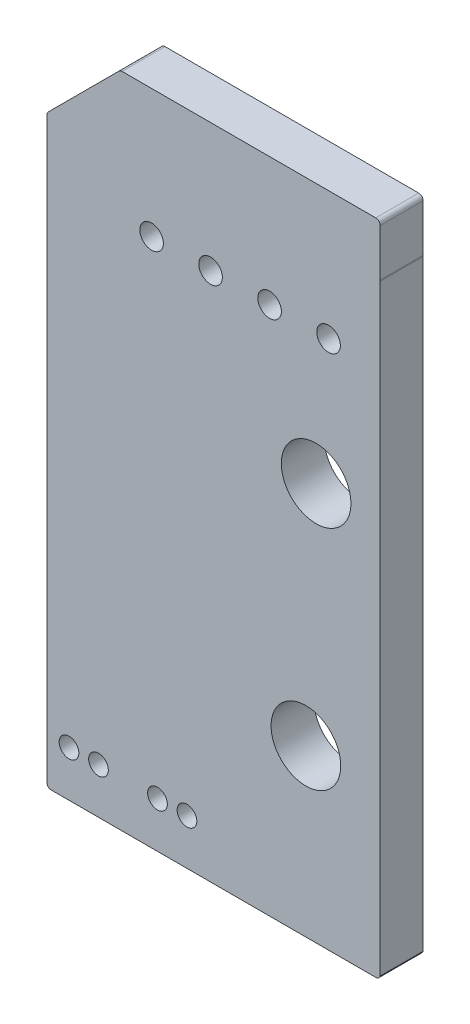
SolidWorks part; units mm, degrees
ref_plane "Front Plane" through (0, 0, 0) normal (0, 0, 1) x (1, 0, 0)
ref_plane "Top Plane" through (0, 0, 0) normal (0, 1, 0) x (1, 0, 0)
ref_plane "Right Plane" through (0, 0, 0) normal (1, 0, 0) x (0, 0, -1)
sketch "Sketch1" plane through (0, 0, 0) normal (0, 0, 1) x (1, 0, 0)
  line L0 (1415.2448, -839.5945) -> (1429.2148, -839.5945)
  line L1 (1415.2448, -839.2135) -> (1429.2148, -839.2135)
  line L2 (1415.4353, -839.404) -> (1415.4353, -814.512)
  line L3 (1415.0543, -839.404) -> (1415.0543, -814.512)
  line L4 (1418.2928, -811.6545) -> (1429.2148, -811.6545)
  line L5 (1418.2928, -811.2735) -> (1429.2148, -811.2735)
  line L6 (1415.3795, -814.6467) -> (1418.4275, -811.5987)
  line L7 (1415.1101, -814.3773) -> (1418.1581, -811.3293)
  line L8 (1429.4053, -813.496) -> (1429.4053, -811.464)
  line L9 (1429.0243, -813.496) -> (1429.0243, -811.464)
  line L10 (1429.3977, -839.4624) -> (1429.3977, -813.463)
  line L11 (1429.0167, -839.4624) -> (1429.0167, -813.463)
  line L12 (1415.7071, -837.3263) -> (1416.3065, -837.9257)
  line L13 (1416.3065, -837.3263) -> (1415.7071, -837.9257)
  line L14 (1416.9771, -837.3263) -> (1417.5765, -837.9257)
  line L15 (1417.5765, -837.3263) -> (1416.9771, -837.9257)
  line L16 (1419.5171, -837.3263) -> (1420.1165, -837.9257)
  line L17 (1420.1165, -837.3263) -> (1419.5171, -837.9257)
  line L18 (1420.7871, -837.3263) -> (1421.3865, -837.9257)
  line L19 (1421.3865, -837.3263) -> (1420.7871, -837.9257)
  line L20 (1419.5628, -816.29) -> (1419.5628, -817.306)
  line L21 (1419.0548, -816.798) -> (1420.0708, -816.798)
  line L22 (1422.1028, -816.29) -> (1422.1028, -817.306)
  line L23 (1421.5948, -816.798) -> (1422.6108, -816.798)
  line L24 (1424.6428, -816.29) -> (1424.6428, -817.306)
  line L25 (1424.1348, -816.798) -> (1425.1508, -816.798)
  line L26 (1427.1828, -816.29) -> (1427.1828, -817.306)
  line L27 (1426.6748, -816.798) -> (1427.6908, -816.798)
  line L28 (1427.268, -823.5228) -> (1427.268, -821.4016)
  line L29 (1427.268, -821.4016) -> (1425.1469, -821.4016)
  line L30 (1425.1469, -821.4016) -> (1425.1469, -823.5228)
  line L31 (1425.1469, -823.5228) -> (1427.268, -823.5228)
  line L32 (1427.268, -833.5228) -> (1427.268, -831.4016)
  line L33 (1427.268, -831.4016) -> (1425.1469, -831.4016)
  line L34 (1425.1469, -831.4016) -> (1425.1469, -833.5228)
  line L35 (1425.1469, -833.5228) -> (1427.268, -833.5228)
  line L36 (-6.985, -14.1313) -> (6.985, -14.1313)
  line L39 (-7.1755, -13.9408) -> (-7.1755, 10.9512)
  line L41 (-3.937, 14.1897) -> (6.985, 14.1897)
  line L43 (-7.1197, 11.0859) -> (-4.0717, 14.1339)
  line L44 (7.1755, 11.9672) -> (7.1755, 13.9992)
  line L46 (7.1679, -13.9992) -> (7.1679, 11.9139)
  line L48 (-6.5227, -11.8631) -> (-5.9233, -12.4625) construction
  line L49 (-5.9233, -11.8631) -> (-6.5227, -12.4625) construction
  line L50 (-5.2527, -11.8631) -> (-4.6533, -12.4625) construction
  line L51 (-4.6533, -11.8631) -> (-5.2527, -12.4625) construction
  line L52 (-2.7127, -11.8631) -> (-2.1133, -12.4625) construction
  line L53 (-2.1133, -11.8631) -> (-2.7127, -12.4625) construction
  line L54 (-1.4427, -11.8631) -> (-0.8433, -12.4625) construction
  line L55 (-0.8433, -11.8631) -> (-1.4427, -12.4625) construction
  line L56 (-2.667, 9.1732) -> (-2.667, 8.1572) construction
  line L57 (-3.175, 8.6652) -> (-2.159, 8.6652) construction
  line L58 (-0.127, 9.1732) -> (-0.127, 8.1572) construction
  line L59 (-0.635, 8.6652) -> (0.381, 8.6652) construction
  line L60 (2.413, 9.1732) -> (2.413, 8.1572) construction
  line L61 (1.905, 8.6652) -> (2.921, 8.6652) construction
  line L62 (4.953, 9.1732) -> (4.953, 8.1572) construction
  line L63 (4.445, 8.6652) -> (5.461, 8.6652) construction
  line L64 (5.9169, 1.9404) -> (5.9169, 3.001) construction
  line L65 (5.9169, 3.001) -> (2.9171, 3.001) construction
  line L66 (2.9171, 3.001) -> (2.9171, 1.9404) construction
  line L67 (2.9171, 1.9404) -> (5.9169, 1.9404) construction
  line L68 (5.0382, -8.0596) -> (5.0382, -5.9384) construction
  line L69 (5.0382, -5.9384) -> (2.9171, -5.9384) construction
  line L70 (2.9171, -5.9384) -> (2.9171, -8.0596) construction
  line L71 (2.9171, -8.0596) -> (5.0382, -8.0596) construction
  arc A0 (1429.2148, -839.5945) -> (1429.2148, -839.2135) centre (1429.2148, -839.404) ccw
  arc A1 (1415.2448, -839.2135) -> (1415.2448, -839.5945) centre (1415.2448, -839.404) ccw
  arc A2 (1415.4353, -814.512) -> (1415.0543, -814.512) centre (1415.2448, -814.512) ccw
  arc A3 (1415.0543, -839.404) -> (1415.4353, -839.404) centre (1415.2448, -839.404) ccw
  arc A4 (1429.2148, -811.6545) -> (1429.2148, -811.2735) centre (1429.2148, -811.464) ccw
  arc A5 (1418.2928, -811.2735) -> (1418.2928, -811.6545) centre (1418.2928, -811.464) ccw
  arc A6 (1418.4275, -811.5987) -> (1418.1581, -811.3293) centre (1418.2928, -811.464) ccw
  arc A7 (1415.1101, -814.3773) -> (1415.3795, -814.6467) centre (1415.2448, -814.512) ccw
  arc A8 (1429.4053, -811.464) -> (1429.0243, -811.464) centre (1429.2148, -811.464) ccw
  arc A9 (1429.0243, -813.496) -> (1429.4053, -813.496) centre (1429.2148, -813.496) ccw
  arc A10 (1429.3977, -813.463) -> (1429.0167, -813.463) centre (1429.2072, -813.463) ccw
  arc A11 (1429.0167, -839.4624) -> (1429.3977, -839.4624) centre (1429.2072, -839.4624) ccw
  circle A12 centre (1419.7076, -828.162) radius 0.3175
  circle A13 centre (1421.1579, -828.0629) radius 0.3175
  arc A14 (6.985, -14.1313) -> (7.1679, -13.9941) centre (6.985, -13.9408) ccw
  arc A15 (-7.1755, -13.9408) -> (-6.985, -14.1313) centre (-6.985, -13.9408) ccw
  arc A16 (-7.1197, 11.0859) -> (-7.1755, 10.9512) centre (-6.985, 10.9512) ccw
  arc A17 (-7.1755, -13.9408) -> (-6.985, -14.1313) centre (-6.985, -13.9408) ccw
  arc A18 (7.1755, 13.9992) -> (6.985, 14.1897) centre (6.985, 13.9992) ccw
  arc A19 (-3.937, 14.1897) -> (-4.0717, 14.1339) centre (-3.937, 13.9992) ccw
  arc A20 (-3.937, 14.1897) -> (-4.0717, 14.1339) centre (-3.937, 13.9992) ccw
  arc A21 (-7.1197, 11.0859) -> (-7.1755, 10.9512) centre (-6.985, 10.9512) ccw
  arc A22 (7.1755, 13.9992) -> (6.985, 14.1897) centre (6.985, 13.9992) ccw
  arc A23 (7.1679, 11.9139) -> (7.1755, 11.9672) centre (6.985, 11.9672) ccw
  circle A24 centre (-2.667, 8.6652) radius 0.508
  circle A25 centre (-0.127, 8.6652) radius 0.508
  circle A26 centre (4.417, 3.001) radius 1.4999
  circle A27 centre (3.9777, -6.999) radius 1.4999
  circle A28 centre (2.413, 8.6652) radius 0.508
  circle A29 centre (4.953, 8.6652) radius 0.508
  circle A30 centre (-6.223, -12.1628) radius 0.4238
  circle A31 centre (-4.953, -12.1628) radius 0.4238
  circle A32 centre (-2.413, -12.1628) radius 0.4238
  circle A33 centre (-1.143, -12.1628) radius 0.4238
extrude "Boss-Extrude1" add sketch "Sketch1" along normal blind 1.85 contours L46 A23 L44 A18 L41 A19 L43 A16 L39 A15 L36 A14 A33 A32 A31 A30 A29 A28 A27 A26 A25 A24
